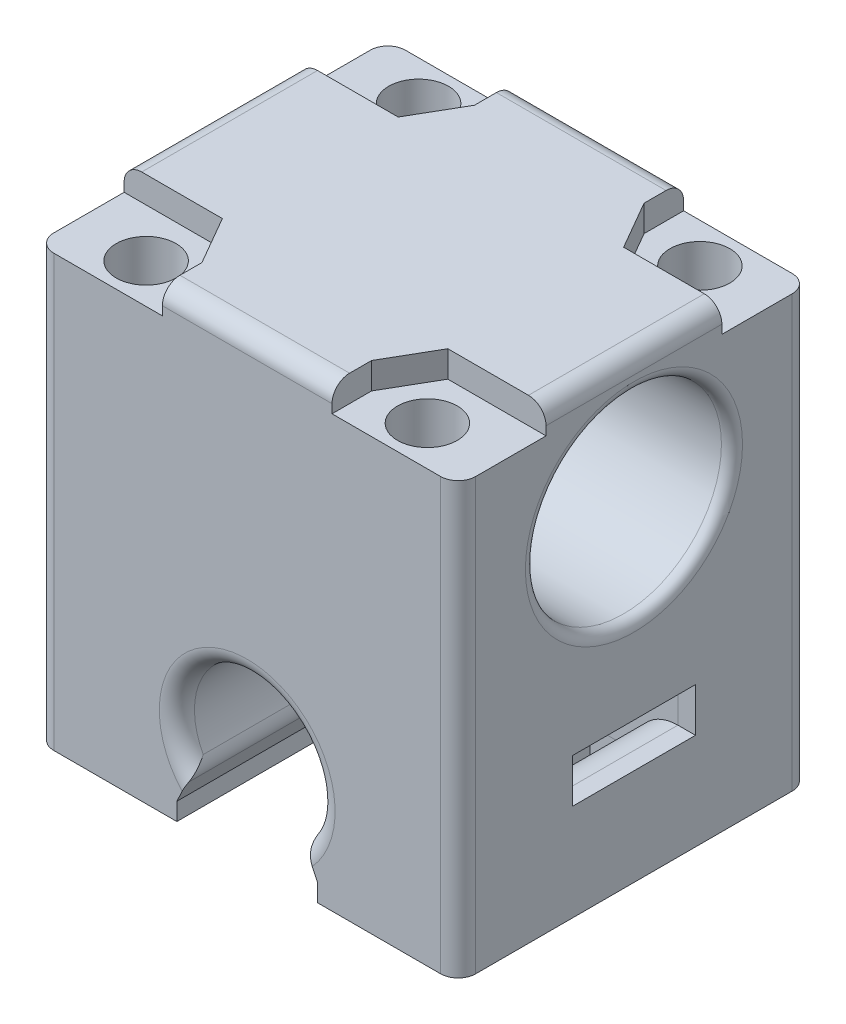
SolidWorks part; units mm, degrees
ref_plane "Alzado" through (0, 0, 0) normal (0, 0, 1) x (1, 0, 0)
ref_plane "Planta" through (0, 0, 0) normal (0, 1, 0) x (1, 0, 0)
ref_plane "Vista lateral" through (0, 0, 0) normal (1, 0, 0) x (0, 0, -1)
sketch "Croquis1" plane through (0, 0, 0) normal (0, -1, 0) x (1, 0, 0)
  line L1 (26.4565, 24.3192) -> (50.4565, 24.3192)
  line L2 (26.4565, 24.3192) -> (26.4565, 4.3192)
  line L3 (26.4565, 4.3192) -> (50.4565, 4.3192)
  line L4 (50.4565, 24.3192) -> (50.4565, 4.3192)
  dimension "D1" = 24
  dimension "D2" = 20
extrude "Saliente-Extruir1" add sketch "Croquis1" against normal blind 25 separate body
sketch "Croquis2" plane through (0, 0, 24.3192) normal (0, 0, 1) x (1, 0, 0)
  line L0 (34.4565, 0) -> (35.2248, 1.6428)
  line L2 (41.6881, 1.6428) -> (42.4565, 0)
  line L3 (42.4565, 0) -> (34.4565, 0)
  line L5 (50.4565, 25) -> (50.4565, 0) construction
  line L6 (50.4565, 0) -> (26.4565, 0) construction
  arc A0 (41.6881, 1.6428) -> (35.2248, 1.6428) centre (38.4565, 4) ccw
  dimension "D1" = 4
  dimension "D2" = 8
  dimension "D3" = 12
  dimension "D6" = 25
  dimension "D7" = 4
  dimension "D8" = 50.132
extrude "Cortar-Extruir1" cut sketch "Croquis2" against normal through all
sketch "Croquis3" plane through (50.4565, 0, 0) normal (1, 0, 0) x (0, 0, -1)
  line L0 (-4.3192, 0) -> (-24.3192, 0) construction
  line L1 (-4.3192, 25) -> (-4.3192, 0) construction
  circle A0 centre (-14.3192, 17.5) radius 5.575
  dimension "D1" = 11.15
  dimension "D2" = 10
  dimension "D3" = 17.5
sketch "Croquis4" plane through (0, 0, 0) normal (0, -1, 0) x (1, 0, 0)
  line L0 (38.4565, 34.8249) -> (38.4565, -1.1794) construction
  line L2 (95.5089, 14.3192) -> (58.9949, 14.3192) construction
  line L4 (26.4565, 24.3192) -> (26.4565, 4.3192) construction
  line L6 (34.4565, 4.3192) -> (34.4565, 24.3192) construction
  circle A0 centre (30.4565, 22.0692) radius 1.7
  circle A1 centre (46.4565, 22.0692) radius 1.7
  circle A2 centre (46.4565, 6.5692) radius 1.7
  circle A3 centre (30.4565, 6.5692) radius 1.7
  dimension "D1" = 12
  dimension "D3" = 3.4
  dimension "D2" = 10
  dimension "D4" = 12
  dimension "D5" = 2.25
extrude "Cortar-Extruir3" cut sketch "Croquis4" against normal through all
sketch "Croquis8" plane through (50.4565, 0, 0) normal (1, 0, 0) x (0, 0, -1)
  line L1 (-17.8192, 7) -> (-10.8192, 7)
  line L2 (-17.8192, 7) -> (-17.8192, 4.5)
  line L3 (-17.8192, 4.5) -> (-10.8192, 4.5)
  line L4 (-10.8192, 7) -> (-10.8192, 4.5)
  line L5 (-4.3192, 0) -> (-24.3192, 0) construction
  dimension "D1" = 7
  dimension "D2" = 2.5
  dimension "D3" = 6.5
  dimension "D4" = 4.5
ref_plane "Plano1" through (0, 0, 10.8192) normal (0, 0, -1) x (-1, 0, 0)
sketch "Croquis9" plane through (0, 0, 10.8192) normal (0, 0, -1) x (-1, 0, 0)
  line L0 (-42.4565, 0) -> (-50.4565, 0) construction
  line L1 (-49.4565, 7) -> (-50.4565, 7)
  line L2 (-44.4565, 2) -> (-44.4565, 0)
  line L3 (-50.4565, 25) -> (-50.4565, 0) construction
  arc A0 (-44.4565, 2) -> (-49.4565, 7) centre (-49.4565, 2) ccw
  dimension "D1" = 5
  dimension "D2" = 2
  dimension "D3" = 1
sweep "Cortar-Barrer2" cut profiles "Croquis8" path "Croquis9"
ref_plane "Plano2" through (38.4565, 0, 0) normal (1, 0, 0) x (0, 0, -1)
mirror "Simetría1" about plane through (38.4565, 0, 0) normal (1, 0, 0) of "Cortar-Barrer2"
sketch "Croquis11" plane through (0, 25, 0) normal (0, 1, 0) x (1, 0, 0)
  line L0 (50.4565, -24.3192) -> (26.4565, -24.3192) construction
  line L1 (48.0442, -19.3192) -> (44.8688, -19.3192)
  line L2 (44.8688, -19.3192) -> (43.281, -22.0692)
  line L3 (43.281, -22.0692) -> (44.8688, -24.8192) construction
  line L4 (44.8688, -24.8192) -> (48.0442, -24.8192) construction
  line L5 (48.0442, -24.8192) -> (49.6319, -22.0692) construction
  line L6 (49.6319, -22.0692) -> (48.0442, -19.3192) construction
  line L7 (26.4565, -4.3192) -> (50.4565, -4.3192) construction
  line L8 (27.281, -22.0692) -> (28.8688, -19.3192) construction
  line L9 (28.8688, -24.8192) -> (27.281, -22.0692) construction
  line L10 (32.0442, -24.8192) -> (28.8688, -24.8192) construction
  line L11 (33.6319, -22.0692) -> (32.0442, -24.8192) construction
  line L12 (26.4565, -24.3192) -> (33.6319, -24.3192)
  line L13 (26.4565, -19.3192) -> (26.4565, -24.3192)
  line L14 (28.8688, -19.3192) -> (26.4565, -19.3192)
  line L15 (33.6319, -22.0692) -> (33.6319, -24.3192)
  line L16 (32.0442, -19.3192) -> (33.6319, -22.0692)
  line L17 (28.8688, -19.3192) -> (32.0442, -19.3192)
  line L18 (33.6319, -6.5692) -> (32.0442, -3.8192) construction
  line L19 (32.0442, -3.8192) -> (28.8688, -3.8192) construction
  line L20 (28.8688, -3.8192) -> (27.281, -6.5692) construction
  line L21 (27.281, -6.5692) -> (28.8688, -9.3192) construction
  line L22 (49.6319, -6.5692) -> (48.0442, -9.3192) construction
  line L23 (48.0442, -3.8192) -> (49.6319, -6.5692) construction
  line L24 (44.8688, -3.8192) -> (48.0442, -3.8192) construction
  line L25 (43.281, -6.5692) -> (44.8688, -3.8192) construction
  line L26 (26.4565, -14.3192) -> (50.4565, -14.3192) construction
  line L27 (43.281, -22.0692) -> (43.281, -24.3192)
  line L28 (48.0442, -19.3192) -> (50.4565, -19.3192)
  line L29 (50.4565, -4.3192) -> (50.4565, -24.3192) construction
  line L30 (50.4565, -19.3192) -> (50.4565, -24.3192)
  line L31 (50.4565, -24.3192) -> (43.281, -24.3192)
  line L32 (26.4565, -24.3192) -> (26.4565, -4.3192) construction
  line L33 (38.4565, -4.3192) -> (38.4565, -24.3192) construction
  line L34 (50.4565, -4.3192) -> (43.281, -4.3192)
  line L35 (50.4565, -9.3192) -> (50.4565, -4.3192)
  line L36 (48.0442, -9.3192) -> (50.4565, -9.3192)
  line L37 (43.281, -6.5692) -> (43.281, -4.3192)
  line L38 (28.8688, -9.3192) -> (32.0442, -9.3192)
  line L39 (32.0442, -9.3192) -> (33.6319, -6.5692)
  line L40 (33.6319, -6.5692) -> (33.6319, -4.3192)
  line L41 (28.8688, -9.3192) -> (26.4565, -9.3192)
  line L42 (26.4565, -9.3192) -> (26.4565, -4.3192)
  line L43 (26.4565, -4.3192) -> (33.6319, -4.3192)
  line L44 (44.8688, -9.3192) -> (43.281, -6.5692)
  line L45 (48.0442, -9.3192) -> (44.8688, -9.3192)
  circle A0 centre (30.4565, -6.5692) radius 2.75 construction
  dimension "D1" = 5.5
extrude "Cortar-Extruir7" cut sketch "Croquis11" against normal blind 1.5
extrude "Cortar-Extruir8" cut sketch "Croquis3" against normal blind 40
sketch "Croquis13" plane through (0, 0, 0) normal (0, -1, 0) x (1, 0, 0)
  line L1 (50.4565, 24.3192) -> (42.4565, 24.3192)
  line L2 (50.4565, 24.3192) -> (50.4565, 4.3192)
  line L3 (50.4565, 4.3192) -> (42.4565, 4.3192)
  line L4 (42.4565, 24.3192) -> (42.4565, 4.3192)
  line L5 (46.9565, 17.8192) -> (44.4565, 17.8192)
  line L6 (46.9565, 17.8192) -> (46.9565, 10.8192)
  line L7 (46.9565, 10.8192) -> (44.4565, 10.8192)
  line L8 (44.4565, 17.8192) -> (44.4565, 10.8192)
  circle A0 centre (46.4565, 22.0692) radius 1.7
  circle A1 centre (46.4565, 6.5692) radius 1.7
extrude "Saliente-Extruir2" add sketch "Croquis13" along normal blind 1
sketch "Croquis14" plane through (0, 0, 0) normal (0, -1, 0) x (1, 0, 0)
  line L1 (34.4565, 24.3192) -> (26.4565, 24.3192)
  line L2 (34.4565, 24.3192) -> (34.4565, 4.3192)
  line L3 (34.4565, 4.3192) -> (26.4565, 4.3192)
  line L4 (26.4565, 24.3192) -> (26.4565, 4.3192)
  line L5 (32.4565, 17.8192) -> (29.9565, 17.8192)
  line L6 (32.4565, 17.8192) -> (32.4565, 10.8192)
  line L7 (32.4565, 10.8192) -> (29.9565, 10.8192)
  line L8 (29.9565, 17.8192) -> (29.9565, 10.8192)
  circle A0 centre (30.4565, 22.0692) radius 1.7
  circle A1 centre (30.4565, 6.5692) radius 1.7
extrude "Saliente-Extruir3" add sketch "Croquis14" along normal blind 1
fillet "Redondeo1" radius 1 12 edges at (38.4565, 25, 24.3192) (38.4565, 25, 4.3192) (26.4565, 25, 14.3192) (26.4565, 11.25, 4.3192) (26.4565, 11.25, 24.3192) (50.4565, 11.25, 4.3192) (50.4565, 25, 14.3192) (50.4565, 11.25, 24.3192) (41.6881, 1.6428, 14.3192) (35.2248, 1.6428, 14.3192) (38.4565, 8, 4.3192) (38.4565, 8, 24.3192)
fillet "Redondeo3" radius 0.6 2 edges at (50.4565, 17.5, 8.7442) (26.4565, 17.5, 19.8942)
